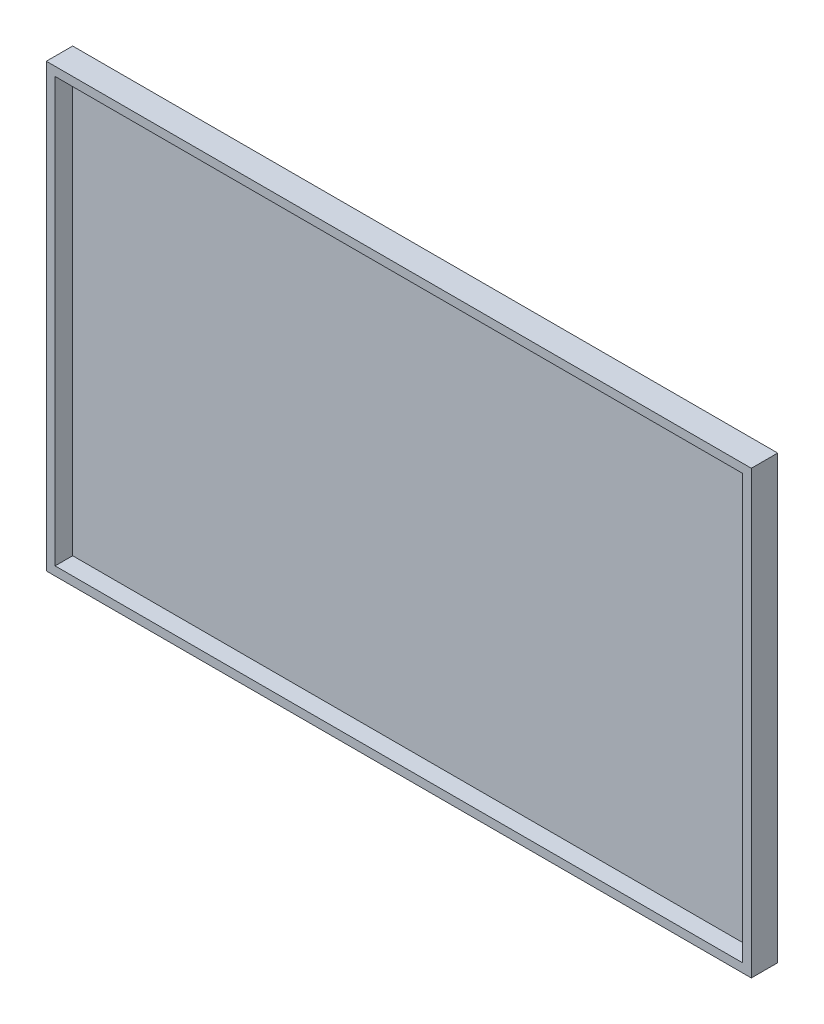
SolidWorks part; units mm, degrees
ref_plane "Plan de face" through (0, 0, 0) normal (0, 0, 1) x (1, 0, 0)
ref_plane "Plan de dessus" through (0, 0, 0) normal (0, 1, 0) x (1, 0, 0)
ref_plane "Plan de droite" through (0, 0, 0) normal (1, 0, 0) x (0, 0, -1)
sketch "Esquisse1" plane through (0, 0, 0) normal (0, 0, 1) x (1, 0, 0)
  line L1 (-51.1381, 30.218) -> (109.3619, 30.218)
  line L2 (-51.1381, 30.218) -> (-51.1381, -70.282)
  line L3 (-51.1381, -70.282) -> (109.3619, -70.282)
  line L4 (109.3619, 30.218) -> (109.3619, -70.282)
  dimension "D1" = 160.5
  dimension "D2" = 100.5
extrude "Boss.-Extru.1" add sketch "Esquisse1" along normal blind 2
sketch "Esquisse2" plane through (0, 0, 2) normal (0, 0, 1) x (1, 0, 0)
  line L1 (-51.1381, 30.218) -> (109.3619, 30.218)
  line L2 (-51.1381, 30.218) -> (-51.1381, -70.282)
  line L3 (-51.1381, -70.282) -> (109.3619, -70.282)
  line L4 (109.3619, 30.218) -> (109.3619, -70.282)
  line L5 (-49.1381, 28.218) -> (107.3619, 28.218)
  line L6 (-49.1381, 28.218) -> (-49.1381, -68.282)
  line L7 (-49.1381, -68.282) -> (107.3619, -68.282)
  line L8 (107.3619, 28.218) -> (107.3619, -68.282)
  dimension "D1" = 2
  dimension "D2" = 2
  dimension "D3" = 2
  dimension "D4" = 2
extrude "Boss.-Extru.2" add sketch "Esquisse2" along normal blind 4
